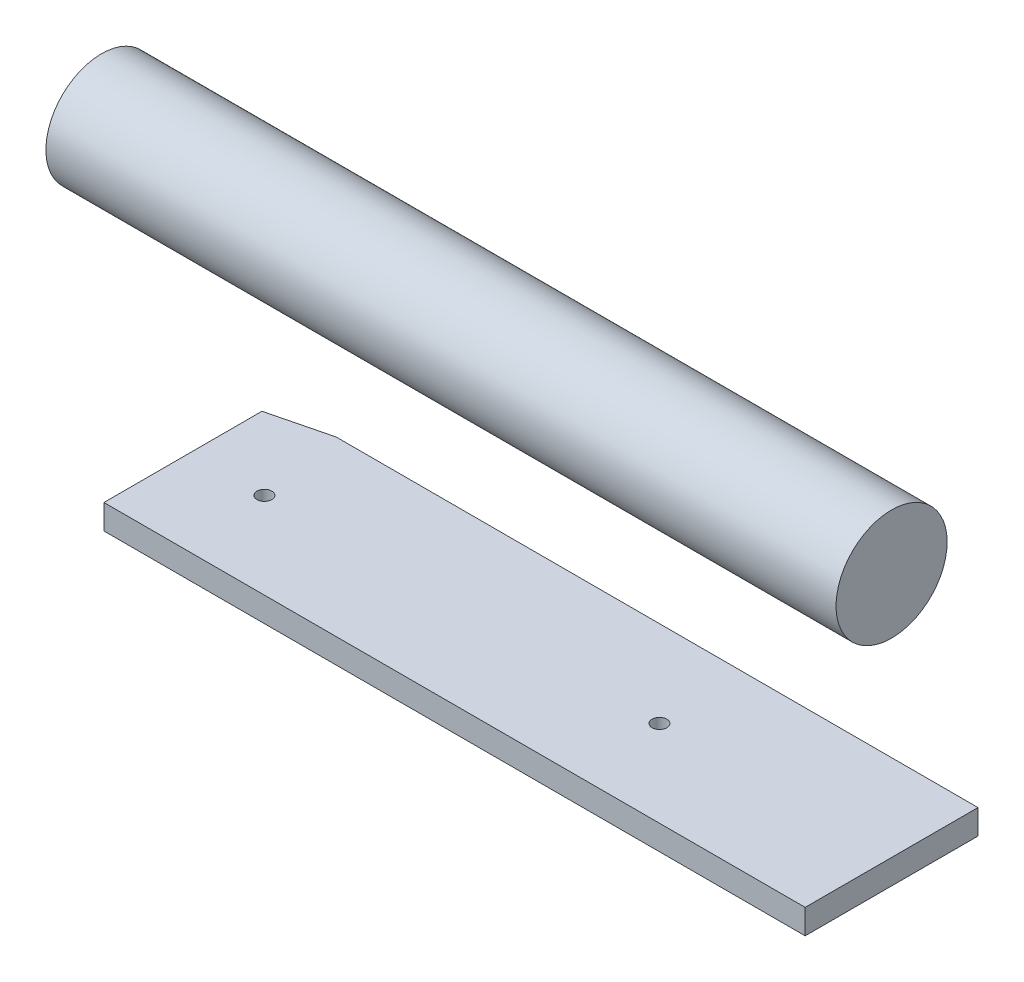
SolidWorks part; units mm, degrees
ref_plane "Front Plane" through (0, 0, 0) normal (0, 0, 1) x (1, 0, 0)
ref_plane "Top Plane" through (0, 0, 0) normal (0, 1, 0) x (1, 0, 0)
ref_plane "Right Plane" through (0, 0, 0) normal (1, 0, 0) x (0, 0, -1)
sketch "Sketch1" plane through (0, 0, 0) normal (1, 0, 0) x (0, 0, -1)
  circle A0 centre (0, 54.7) radius 11.25
  dimension "D2" = 22.5
  dimension "D1" = 54.7
extrude "Boss-Extrude1" add sketch "Sketch1" along normal blind 160
sketch "Sketch2" plane through (160, 0, 0) normal (1, 0, 0) x (0, 0, -1)
  line L1 (17.5, 0) -> (-17.5, 0)
  line L2 (-17.5, 0) -> (-17.5, 80)
  line L3 (-17.5, 80) -> (17.5, 80)
  line L4 (17.5, 80) -> (17.5, 0)
  dimension "D1" = 35
  dimension "D2" = 80
sketch "Sketch3" plane through (0, 0, 0) normal (0, 1, 0) x (1, 0, 0)
  line L0 (160, 17.5) -> (30.0323, 17.5)
  line L1 (160, 17.5) -> (160, -17.5) construction
  line L2 (-51.2102, 0) -> (260.5349, 0) construction
  line L3 (18, -17.5) -> (160, -17.5)
  line L4 (160, -17.5) -> (160, 17.5) construction
  line L5 (160, -17.5) -> (160, 17.5)
  line L6 (18, 14.5) -> (18, -17.5)
  line L7 (18, 14.5) -> (30.0323, 17.5)
  circle A0 centre (33, 0) radius 1.5
  circle A1 centre (113, 0) radius 1.5
  dimension "D2" = 3
  dimension "D5" = 3
  dimension "D1" = 142
  dimension "D3" = 15
  dimension "D4" = 80
extrude "Boss-Extrude2" add sketch "Sketch3" along normal blind 5 separate body
sketch "Sketch5" plane through (0, 0, 0) normal (0, -1, 0) x (1, 0, 0)
  line L0 (0, 0) -> (160, 0)
  line L1 (160, 17.5) -> (160, -17.5) construction
  line L2 (160, 17.5) -> (160, -17.5)
  point P8 (160, 0)
  point P9 (160, -17.5)
  point P10 (160, 17.5)
sketch "Sketch6" plane through (0, 0, 0) normal (0, 0, 1) x (1, 0, 0)
  line L0 (0, 54.7) -> (160, 54.7)
  line L1 (0, 65.95) -> (0, 43.45) construction
  line L2 (160, 43.45) -> (160, 65.95) construction
